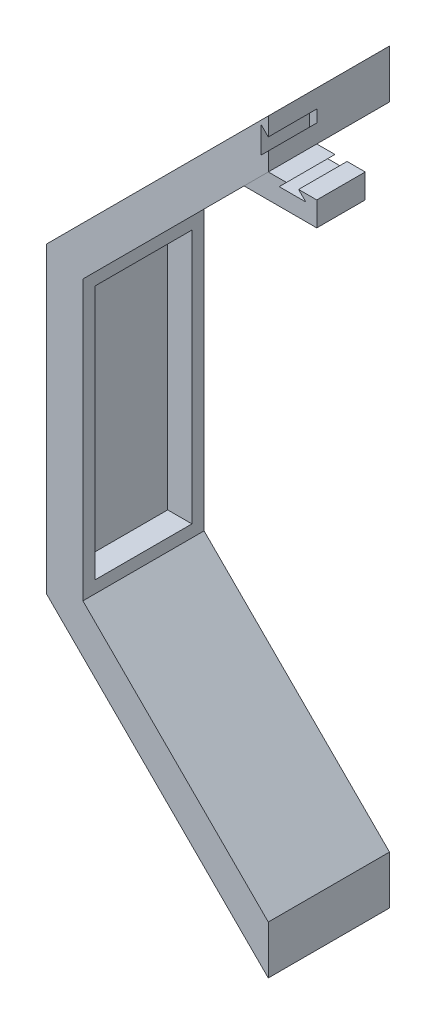
SolidWorks part; units mm, degrees
ref_plane "Plan de face" through (0, 0, 0) normal (0, 0, 1) x (1, 0, 0)
ref_plane "Plan de dessus" through (0, 0, 0) normal (0, 1, 0) x (1, 0, 0)
ref_plane "Plan de droite" through (0, 0, 0) normal (1, 0, 0) x (0, 0, -1)
sketch "Esquisse1" plane through (0, 0, 0) normal (0, 0, 1) x (1, 0, 0)
  line L0 (0, -62.5) -> (0, 62.5)
  line L1 (0, 62.5) -> (91.5, 154)
  line L2 (91.5, 154) -> (91.5, 134)
  line L3 (91.5, -154) -> (0, -62.5)
  line L4 (91.5, 134) -> (15, 57.5)
  line L5 (15, 57.5) -> (15, -57.5)
  line L6 (15, -57.5) -> (91.5, -134)
  line L7 (91.5, -134) -> (91.5, -154)
  point P0 (0, 0)
  dimension "D1" = 308
  dimension "D2" = 135
  dimension "D3" = 125
  dimension "D4" = 15
  dimension "D5" = 20
  dimension "D6" = 135
extrude "Boss.-Extru.1" add sketch "Esquisse1" along normal blind 50
sketch "Esquisse2" plane through (0, 0, 50) normal (0, 0, 1) x (1, 0, 0)
  line L0 (91.5, 134) -> (99, 134)
  line L1 (99, 134) -> (96, 131)
  line L2 (96, 131) -> (107, 131)
  line L3 (107, 131) -> (104, 134)
  line L4 (104, 134) -> (111.5, 134)
  line L5 (111.5, 134) -> (111.5, 124)
  line L6 (111.5, 124) -> (81.5, 124)
  line L7 (15, 57.5) -> (91.5, 134) construction
  line L8 (81.5, 124) -> (91.5, 134)
  dimension "D1" = 5
  dimension "D2" = 20
  dimension "D3" = 10
  dimension "D4" = 3
extrude "Boss.-Extru.2" add sketch "Esquisse2" against normal blind 20 separate body
sketch "Esquisse3" plane through (-21.25, 21.25, 0) normal (0.7071, -0.7071, 0) x (0, 0, -1)
  line L0 (0, 51.2652) -> (0, 159.4526) construction
  line L1 (-5, 51.2652) -> (-45, 51.2652)
  line L2 (-5, 51.2652) -> (-5, 154.4526)
  line L3 (-45, 145.3104) -> (-30, 145.3104)
  line L4 (-45, 51.2652) -> (-45, 145.3104)
  line L6 (-50, 51.2652) -> (0, 51.2652) construction
  line L7 (-50, 51.2652) -> (-50, 159.4526) construction
  line L9 (-30, 145.3104) -> (-30, 154.4526)
  line L10 (-30, 154.4526) -> (-5, 154.4526)
  line L11 (-50, 159.4526) -> (0, 159.4526) construction
  line L12 (-30, 159.4526) -> (-30, 145.3104) construction
  line L13 (-30, 145.3104) -> (-50, 145.3104) construction
  dimension "D1" = 5
  dimension "D2" = 5
  dimension "D3" = 5
extrude "Enlèv. mat.-Extru.1" cut sketch "Esquisse3" against normal blind 10
sketch "Esquisse4" plane through (15, 0, 0) normal (1, 0, 0) x (0, 0, -1)
  line L1 (-5, 52.5) -> (-45, 52.5)
  line L2 (-5, 52.5) -> (-5, -52.5)
  line L3 (-5, -52.5) -> (-45, -52.5)
  line L4 (-45, 52.5) -> (-45, -52.5)
  line L5 (0, -57.5) -> (0, 57.5) construction
  line L6 (-50, -57.5) -> (-50, 57.5) construction
  line L7 (-45, 57.5) -> (-5, 57.5) construction
  line L8 (-50, -57.5) -> (0, -57.5) construction
  dimension "D1" = 5
  dimension "D2" = 5
  dimension "D3" = 5
  dimension "D4" = 5
extrude "Enlèv. mat.-Extru.2" cut sketch "Esquisse4" against normal blind 10
sketch "Esquisse5" plane through (0, 0, 50) normal (0, 0, 1) x (1, 0, 0)
  line L0 (91.5, 146.5) -> (88.5, 149.5)
  line L1 (91.5, 134) -> (91.5, 154) construction
  line L2 (88.5, 149.5) -> (88.5, 138.5)
  line L3 (88.5, 138.5) -> (91.5, 141.5)
  line L4 (91.5, 141.5) -> (91.5, 146.5)
  point P5 (91.5, 144)
  dimension "D1" = 5
  dimension "D2" = 3
  dimension "D3" = 135
extrude "Enlèv. mat.-Extru.3" cut sketch "Esquisse5" against normal blind 20
